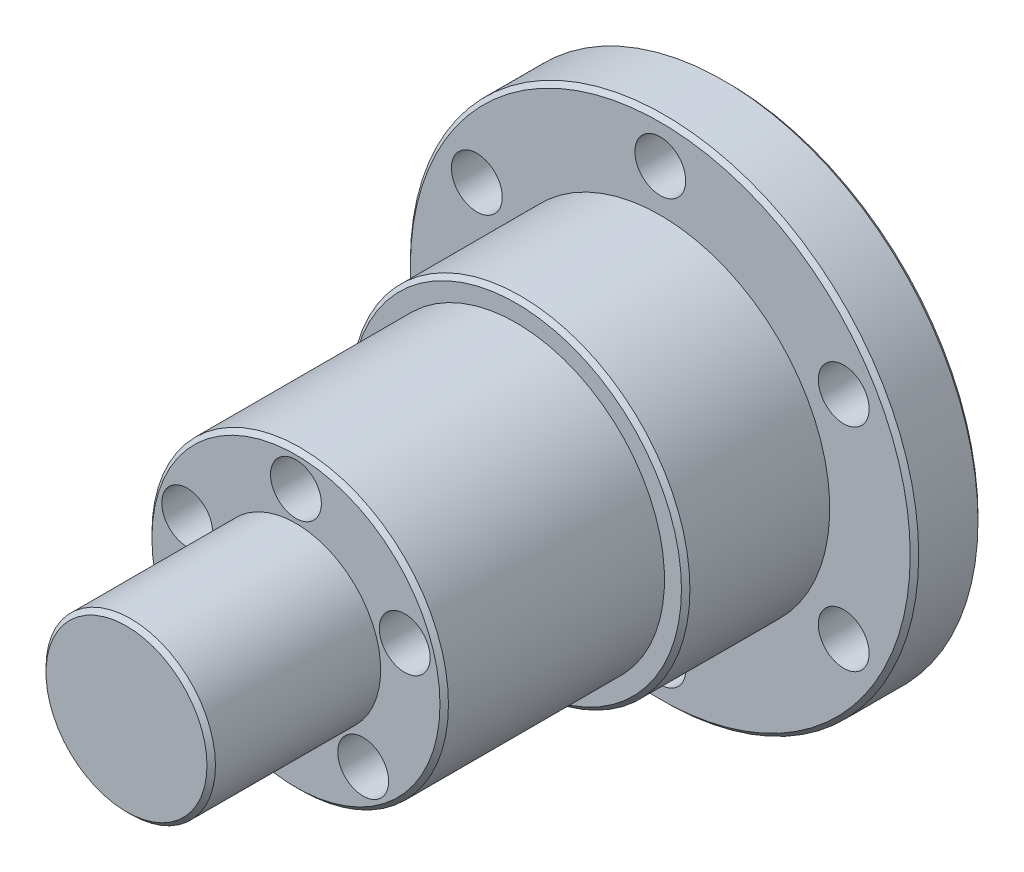
SolidWorks part; units mm, degrees
ref_plane "前视基准面" through (0, 0, 0) normal (0, 0, 1) x (1, 0, 0)
ref_plane "上视基准面" through (0, 0, 0) normal (0, 1, 0) x (1, 0, 0)
ref_plane "右视基准面" through (0, 0, 0) normal (1, 0, 0) x (0, 0, -1)
other "Configuration Table"
sketch "草图1" plane through (0, 0, 0) normal (1, 0, 0) x (0, 0, -1)
  line L0 (0, 0) -> (0, 10)
  line L1 (0, 10) -> (20, 10)
  line L2 (20, 10) -> (20, 17.5)
  line L3 (20, 17.5) -> (46, 17.5)
  line L4 (46, 17.5) -> (46, 20)
  line L5 (46, 20) -> (63, 20)
  line L6 (63, 20) -> (63, 30)
  line L7 (63, 30) -> (71, 30)
  line L8 (71, 30) -> (71, 0)
  line L9 (71, 0) -> (0, 0)
  line L10 (0, 0) -> (-32.0422, 0) construction
  dimension "D1" = 60
  dimension "D2" = 20
  dimension "D3" = 35
  dimension "D4" = 40
  dimension "D5" = 20
  dimension "D6" = 46
  dimension "D7" = 63
  dimension "D8" = 71
revolve "旋转1" add sketch "草图1" angle 360 about L10
sketch "草图2" plane through (0, 0, -71) normal (0, 0, -1) x (-1, 0, 0)
  circle A0 centre (0, 0) radius 25 construction
  circle A1 centre (0, 25) radius 3
  circle A2 centre (21.6506, 12.5) radius 3
  circle A3 centre (21.6506, -12.5) radius 3
  circle A4 centre (0, -25) radius 3
  circle A5 centre (-21.6506, -12.5) radius 3
  circle A6 centre (-21.6506, 12.5) radius 3
  point P5 (21.6491, 12.5026)
  point P6 (0, 0)
  point P18 (0, 0)
  dimension "D1" = 50
  dimension "D2" = 6
  dimension "D3" = 6
extrude "切除-拉伸1" cut sketch "草图2" against normal blind 10
sketch "草图3" plane through (0, 0, -71) normal (0, 0, -1) x (-1, 0, 0)
  circle A0 centre (0, 0) radius 13.5 construction
  dimension "D1" = 27
hole_wizard "M6 六角头螺栓的柱形沉头孔2" positions "草图6" profile "草图7" counterbore size "M6" standard "GB" end condition through all
sketch "草图6" plane through (0, 0, -71) normal (0, 0, -1) x (-1, 0, 0)
  circle A0 centre (0, 0) radius 13.5 construction
  point P0 (0, 13.5)
sketch "草图7" plane through (0, 13.5, -71) normal (1, 0, 0) x (0, 1, 0)
  line L0 (0, 0) -> (0, 71)
  line L1 (0, 71) -> (3, 71)
  line L3 (3, 71) -> (3, 6)
  line L4 (3, 6) -> (5, 6)
  line L5 (5, 6) -> (5, 0)
  line L7 (5, 0) -> (0, 0)
  line L11 (0, -6.35) -> (0, 107.95) construction
  dimension "通孔孔直径" = 6
  dimension "通孔孔深度" = 71
  dimension "柱形沉头孔直径" = 10
  dimension "柱形沉头孔深度" = 6
pattern_circular "阵列(圆周)1" count 5 over 360 about axis through (0, 0, 0) along (0, 0, 1) of "M6 六角头螺栓的柱形沉头孔2"
chamfer "倒角1" distance 0.5 angle 45 5 edges at (-30, 0, -71) (-30, 0, -63) (-20, 0, -46) (-17.5, 0, -20) (-10, 0, 0)
